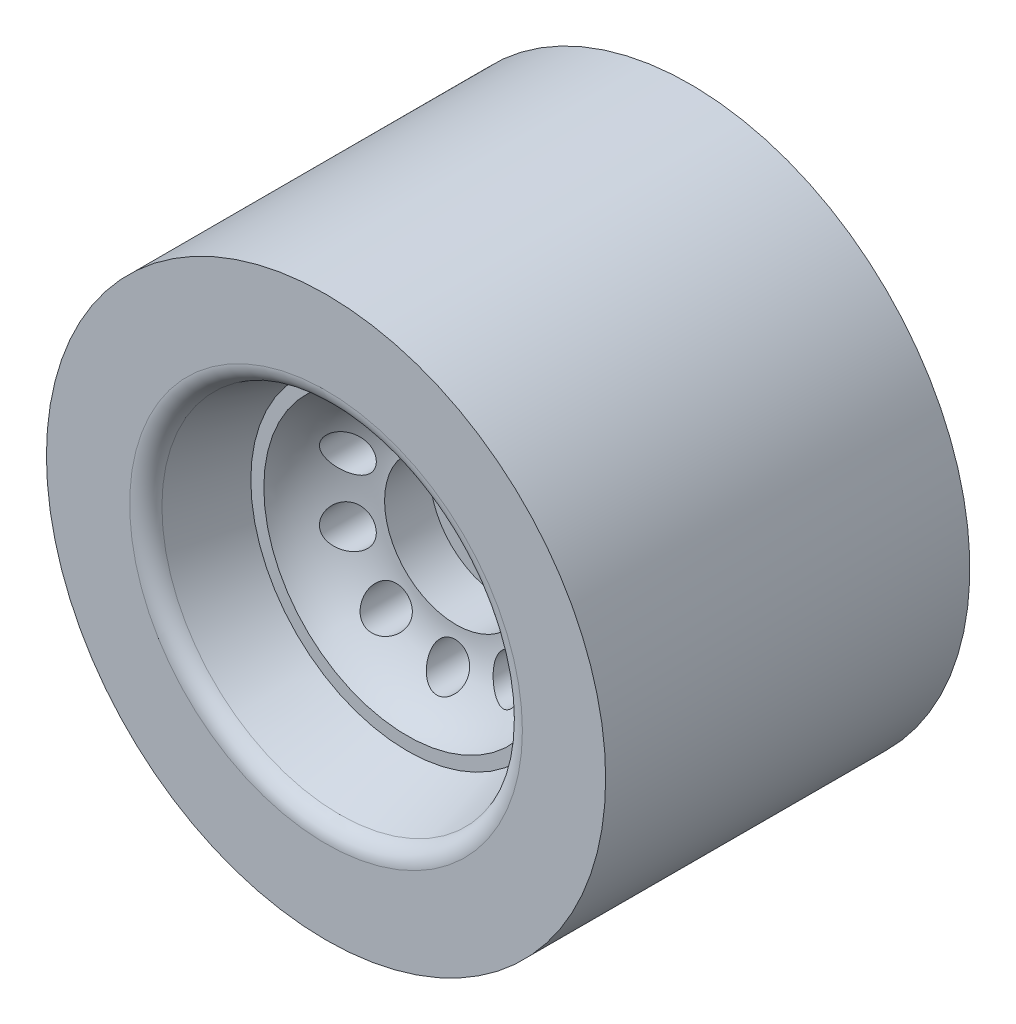
SolidWorks part; units mm, degrees
ref_plane "정면" through (0, 0, 0) normal (0, 0, 1) x (1, 0, 0)
ref_plane "윗면" through (0, 0, 0) normal (0, 1, 0) x (1, 0, 0)
ref_plane "우측면" through (0, 0, 0) normal (1, 0, 0) x (0, 0, -1)
sketch "스케치1" plane through (0, 0, 0) normal (0, 0, 1) x (1, 0, 0)
  circle A0 centre (0, 0) radius 43
  dimension "D1" = 86
extrude "보스-돌출1" add sketch "스케치1" along normal mid plane 56
sketch "스케치2" plane through (0, 0, 28) normal (0, 0, 1) x (1, 0, 0)
  circle A0 centre (0, 0) radius 5
  dimension "D1" = 10
extrude "컷-돌출1" cut sketch "스케치2" against normal through all
sketch "스케치4" plane through (0, 0, 0) normal (1, 0, 0) x (0, 0, -1)
  line L0 (28, 0) -> (-28, 0) construction
  line L1 (28, -43) -> (28, 43) construction
  line L2 (-28, 43) -> (-28, -43) construction
  line L3 (0, 0) -> (0, -43) construction
  line L4 (-28, -43) -> (28, -43) construction
  line L5 (28, 43) -> (27.2, 36.9)
  line L6 (28.7584, 34.5) -> (28.7584, 0) construction
  line L7 (15, 0) -> (28, 0)
  line L8 (15, 0) -> (15, 11)
  line L9 (27.2, 36.9) -> (26.2, 36.4)
  line L10 (28, 0) -> (28, 43)
  line L11 (-28, 0) -> (-28, 28)
  line L12 (-28, 28) -> (-15.5084, 24.06)
  line L13 (-8, 11) -> (-8, 0)
  line L14 (-8, 0) -> (-28, 0)
  line L15 (-15.5084, 24.06) -> (-15.5084, 22.06)
  arc A0 (22.5084, 22.06) -> (24.2345, 28.0809) centre (43.5172, 19.295) cw
  arc A1 (15, 11) -> (22.5084, 22.06) centre (26.9, 11) cw
  arc A2 (24.2345, 28.0809) -> (26.2, 36.4) centre (4.2146, 37.2027) ccw
  arc A3 (-15.5084, 22.06) -> (-8, 11) centre (-19.9, 11) cw
  dimension "D5" = 11.9
  dimension "D4" = 0.5
  dimension "D10" = 6.25
  dimension "D11" = 12.44
  dimension "D9" = 21.19
  dimension "D12" = 22
  dimension "D14" = 15
  dimension "D13" = 11.9
  dimension "D1" = 0.8
  dimension "D2" = 22.06
  dimension "D3" = 6.1
  dimension "D6" = 11
  dimension "D7" = 13
  dimension "D8" = 1
  dimension "D15" = 20
  dimension "D16" = 2
revolve "컷-회전1" cut sketch "스케치4" angle 360 about L0
sketch "스케치5" plane through (0, 0, 0) normal (0, 0, 1) x (1, 0, 0)
  line L0 (0, 0) -> (0, 43) construction
  circle A0 centre (0, 0) radius 43 construction
  circle A1 centre (0, 15.875) radius 3
  dimension "D1" = 6
  dimension "D2" = 15.875
extrude "컷-돌출2" cut sketch "스케치5" against normal through all both and the other way through all
pattern_circular "원형 패턴1" count 10 over 360 about axis through (0, 0, 0) along (0, 0, 1) of "컷-돌출2"
fillet "필렛1" radius 3 1 edges at (-28, 0, 28)
sketch "스케치6" plane through (0, 0, 8) normal (0, 0, 1) x (1, 0, 0)
  circle A0 centre (0, 0) radius 11
  dimension "D1" = 22
extrude "컷-돌출3" cut sketch "스케치6" against normal blind 7
sketch "스케치7" plane through (0, 0, -15) normal (0, 0, -1) x (-1, 0, 0)
  circle A0 centre (0, 0) radius 11
  dimension "D1" = 22
extrude "컷-돌출4" cut sketch "스케치7" against normal blind 7
